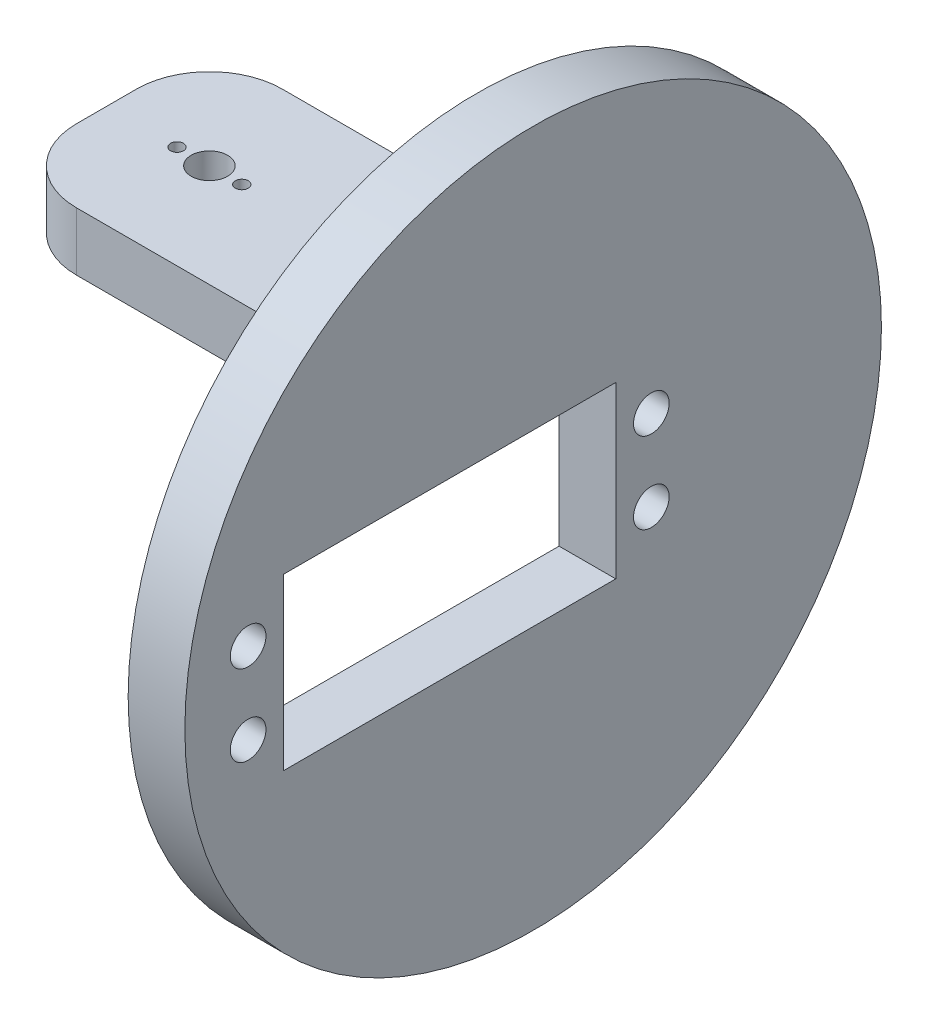
SolidWorks part; units mm, degrees
ref_plane "Front Plane" through (0, 0, 0) normal (0, 0, 1) x (1, 0, 0)
ref_plane "Top Plane" through (0, 0, 0) normal (0, 1, 0) x (1, 0, 0)
ref_plane "Right Plane" through (0, 0, 0) normal (1, 0, 0) x (0, 0, -1)
sketch "Sketch1" plane through (0, 0, 0) normal (0, 1, 0) x (1, 0, 0)
  line L1 (-27.8051, 12.032) -> (17.1949, 12.032)
  line L2 (-27.8051, 12.032) -> (-27.8051, -13.368)
  line L3 (-27.8051, -13.368) -> (17.1949, -13.368)
  line L4 (17.1949, 12.032) -> (17.1949, -13.368)
extrude "Boss-Extrude1" add sketch "Sketch1" along normal blind 7.2
fillet "Fillet1" radius 9 2 edges at (-27.8051, 3.6, 13.368) (-27.8051, 3.6, -12.032)
sketch "Sketch5" plane through (0, 7.2, 0) normal (0, 1, 0) x (1, 0, 0)
  circle A1 centre (-15.1051, -0.668) radius 2.25
  circle A2 centre (-19.1051, -0.668) radius 0.8
  circle A3 centre (-11.1051, -0.668) radius 0.8
extrude "Cut-Extrude1" cut sketch "Sketch5" against normal through all
sketch "Sketch6" plane through (0, 0, 0) normal (0, -1, 0) x (1, 0, 0)
  line L0 (-19.1051, 0.668) -> (-11.1051, 0.668) construction
  line L1 (-19.1051, 3.8183) -> (-11.1051, 3.8183)
  line L2 (-19.1051, -2.4823) -> (-11.1051, -2.4823)
  arc A1 (-19.1051, 3.8183) -> (-19.1051, -2.4823) centre (-19.1051, 0.668) ccw
  arc A2 (-11.1051, -2.4823) -> (-11.1051, 3.8183) centre (-11.1051, 0.668) ccw
  point P7 (-15.1051, 0.668)
extrude "Cut-Extrude2" cut sketch "Sketch6" against normal blind 4
sketch "Sketch7" plane through (17.1949, 0, 0) normal (1, 0, 0) x (0, 0, -1)
  circle A0 centre (0, -12.2514) radius 43
  point P1 (0, 0)
  point P2 (0, 0)
  point P5 (0, 0)
  point P6 (0, -6.0242)
  point P7 (0, -12.2514)
extrude "Boss-Extrude2" add sketch "Sketch7" along normal blind 7
sketch "Sketch10" plane through (24.1949, 0, 0) normal (1, 0, 0) x (0, 0, -1)
  circle A1 centre (0, -12.2514) radius 4.0701
extrude "Cut-Extrude5" cut sketch "Sketch10" against normal up to next
sketch "Sketch11" plane through (17.1949, 0, 0) normal (-1, 0, 0) x (0, 0, 1)
  line L5 (30.8, -22.7514) -> (-10.2, -22.7514)
  line L6 (30.8, -22.7514) -> (30.8, -1.7514)
  line L7 (30.8, -1.7514) -> (-10.2, -1.7514)
  line L8 (-10.2, -22.7514) -> (-10.2, -1.7514)
  line L9 (30.8, -22.7514) -> (-10.2, -1.7514) construction
  line L10 (30.8, -1.7514) -> (-10.2, -22.7514) construction
  circle A0 centre (35.1896, -7.2514) radius 2.2
  circle A1 centre (35.1896, -17.2514) radius 2.2
  circle A2 centre (-14.5896, -7.2514) radius 2.2
  circle A3 centre (-14.5896, -17.2514) radius 2.2
  point P6 (10.3, -12.2514)
extrude "Cut-Extrude6" cut sketch "Sketch11" against normal up to next
